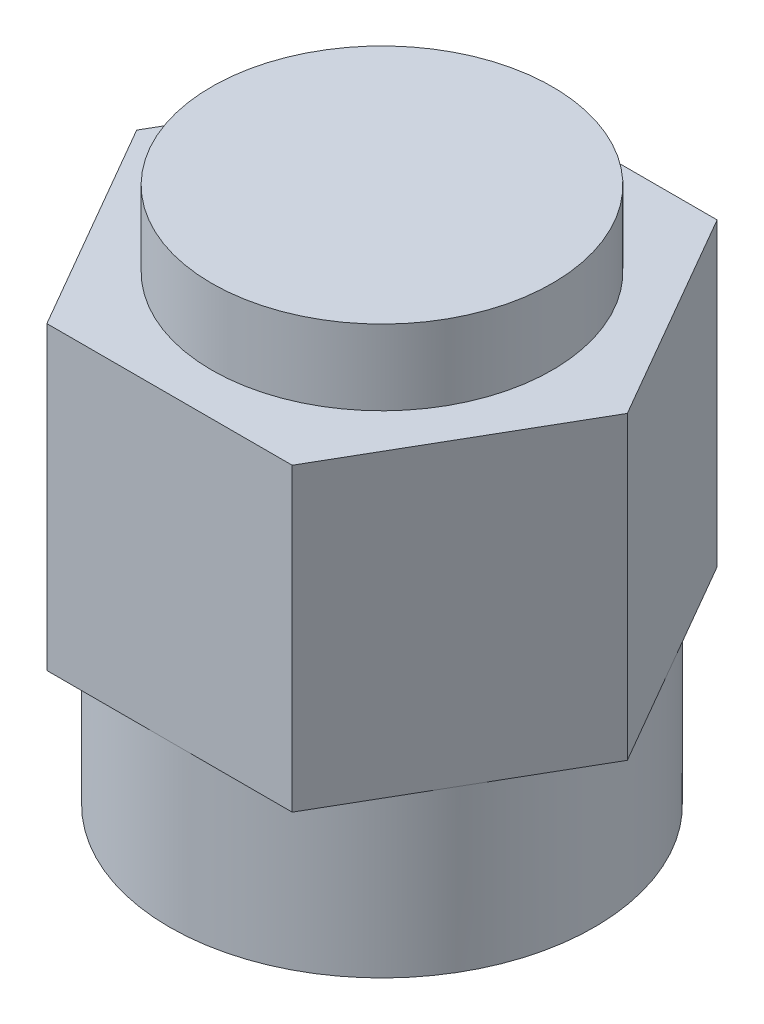
SolidWorks part; units mm, degrees
material "AISI 316 Stainless Steel Sheet (SS)"
ref_plane "Front Plane" through (0, 0, 0) normal (0, 0, 1) x (1, 0, 0)
ref_plane "Top Plane" through (0, 0, 0) normal (0, 1, 0) x (1, 0, 0)
ref_plane "Right Plane" through (0, 0, 0) normal (1, 0, 0) x (0, 0, -1)
sketch "Sketch5" plane through (0, 0, 0) normal (0, 1, 0) x (-1, 0, 0)
  circle A0 centre (0, 0) radius 3.96
  dimension "D1" = 7.92
extrude "Boss-Extrude5" add sketch "Sketch5" along normal blind 3
sketch "Sketch6" plane through (0, 3, 0) normal (0, -1, 0) x (1, 0, 0)
  line L1 (-4.5726, 0) -> (-2.2863, -3.96)
  line L2 (-2.2863, -3.96) -> (2.2863, -3.96)
  line L3 (2.2863, -3.96) -> (4.5726, 0)
  line L4 (4.5726, 0) -> (2.2863, 3.96)
  line L5 (2.2863, 3.96) -> (-2.2863, 3.96)
  line L6 (-2.2863, 3.96) -> (-4.5726, 0)
  circle A0 centre (0, 0) radius 3.175 construction
  circle A1 centre (0, 0) radius 3.96 construction
  circle A2 centre (0, 0) radius 3.96 construction
  dimension "D2" = 7.92
extrude "Boss-Extrude7" add sketch "Sketch6" against normal offset from surface (5.6 mm away) 8.6 up to face at (0, 0, 3.96)
sketch "Sketch7" plane through (0, 0, 0) normal (0, -1, 0) x (1, 0, 0)
  circle A0 centre (0, 0) radius 3.175
  dimension "D1" = 6.35
extrude "Cut-Extrude1" cut sketch "Sketch7" against normal blind 5
sketch "Sketch8" plane through (0, 8.6, 0) normal (0, 1, 0) x (1, 0, 0)
  circle A0 centre (0, 0) radius 3.175
  dimension "D1" = 6.35
extrude "Boss-Extrude9" add sketch "Sketch8" along normal offset from surface (1.4 mm away) 10 up to face at (0, 0, -3.175)
